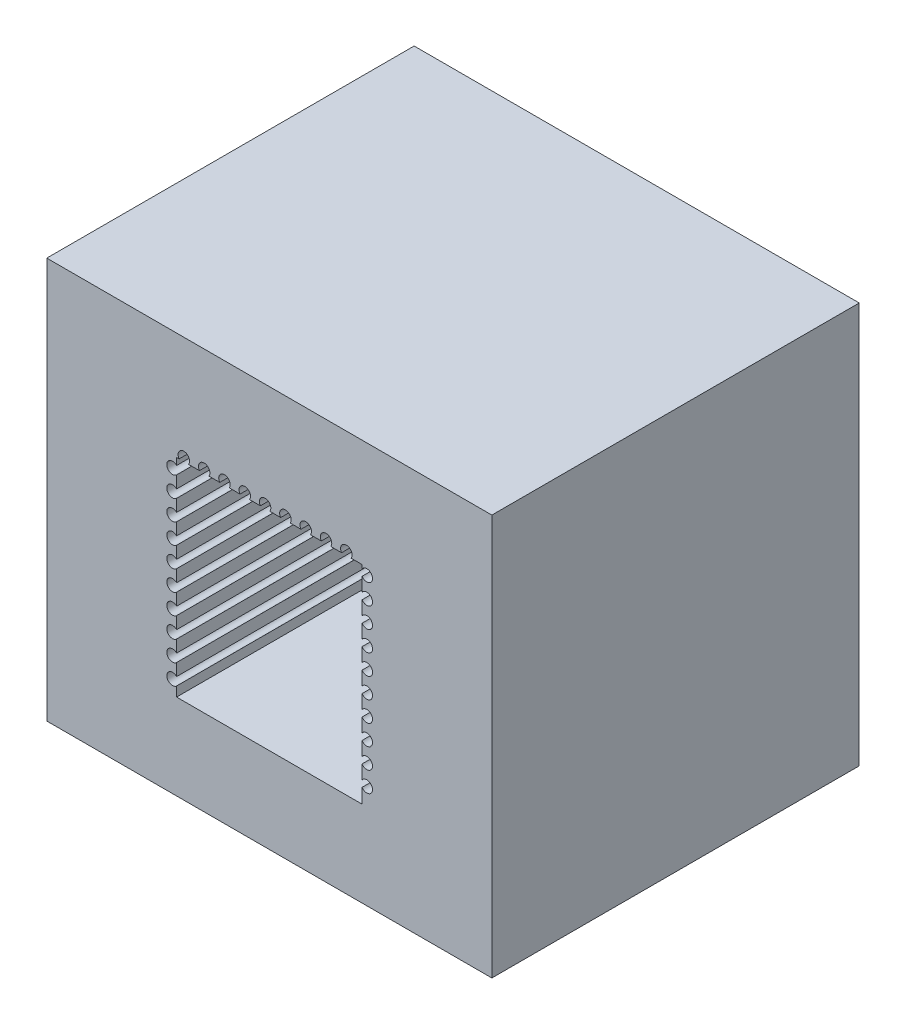
SolidWorks part; units mm, degrees
ref_plane "Front Plane" through (0, 0, 0) normal (0, 0, 1) x (1, 0, 0)
ref_plane "Top Plane" through (0, 0, 0) normal (0, 1, 0) x (1, 0, 0)
ref_plane "Right Plane" through (0, 0, 0) normal (1, 0, 0) x (0, 0, -1)
sketch "Sketch1" plane through (0, 0, 0) normal (0, 0, 1) x (1, 0, 0)
  line L1 (-252, 227) -> (252, 227)
  line L2 (-252, 227) -> (-252, -227)
  line L3 (-252, -227) -> (252, -227)
  line L4 (252, 227) -> (252, -227)
  line L5 (-252, 227) -> (252, -227) construction
  line L6 (-252, -227) -> (252, 227) construction
  point P0 (0, 0)
  dimension "D1" = 504
  dimension "D2" = 454
extrude "Boss-Extrude1" add sketch "Sketch1" against normal blind 416
sketch "Sketch2" plane through (0, 0, 0) normal (0, 0, 1) x (1, 0, 0)
  line L1 (-130, 130) -> (130, 130)
  line L2 (-130, 130) -> (-130, -130)
  line L3 (-130, -130) -> (130, -130)
  line L4 (130, 130) -> (130, -130)
  line L5 (-130, 130) -> (130, -130) construction
  line L6 (-130, -130) -> (130, 130) construction
  point P0 (0, 0)
  dimension "D1" = 260
  dimension "D2" = 260
extrude "Cut-Extrude1" cut sketch "Sketch2" against normal blind 260
sketch "Sketch5" plane through (0, 0, 0) normal (0, 0, 1) x (1, 0, 0)
  line L0 (-130, -130) -> (130, -130) construction
  line L1 (-130, 130) -> (-105, 130)
  line L2 (-130, 130) -> (-130, -130)
  line L3 (-130, -130) -> (-105, -130)
  line L4 (-105, 105) -> (-105, -130)
  line L5 (-130, -130) -> (130, -130) construction
  line L6 (130, 130) -> (105, 130)
  line L7 (130, 130) -> (130, -130)
  line L8 (130, -130) -> (105, -130)
  line L9 (105, 105) -> (105, -130)
  line L10 (-130, 130) -> (130, 130)
  line L11 (-130, 130) -> (130, 130)
  line L12 (-130, 130) -> (-130, 105)
  line L13 (-105, 105) -> (105, 105)
  line L14 (130, 130) -> (130, 105)
  line M1 (130, 130) -> (130, -130)
  line M2 (130, -130) -> (-130, -130)
  line M3 (-130, -130) -> (-130, 130)
  line M4 (-130, 130) -> (130, 130)
  dimension "D1" = 25
  dimension "D2" = 25
  dimension "D3" = 25
extrude "Boss-Extrude2" add sketch "Sketch5" against normal blind 260 contours L4 L13 L9 L7 L2 M2 M1 M4 M3
sketch "Sketch6" plane through (0, 0, 0) normal (0, 0, 1) x (1, 0, 0)
  circle A0 centre (-109.593, 92.4977) radius 6.5
  dimension "D1" = 13
extrude "Cut-Extrude2" cut sketch "Sketch6" against normal blind 260
sketch "Sketch7" plane through (0, 0, 0) normal (0, 0, 1) x (1, 0, 0)
  line L0 (0, 227) -> (0, -130) construction
  line L1 (252, 227) -> (-252, 227) construction
  line L2 (-105, -130) -> (105, -130) construction
  line L3 (-121.2933, 92.4977) -> (0, 92.4977) construction
  circle A0 centre (-109.593, 92.4977) radius 6.5 construction
  circle A1 centre (110.3716, 97.1096) radius 6.5
  dimension "D1" = 13
pattern_linear "LPattern3" count 10 spacing 23 along (0, -1, 0) of "Cut-Extrude2"
extrude "Cut-Extrude3" cut sketch "Sketch7" against normal blind 260
pattern_linear "LPattern4" count 10 spacing 23 along (0, -1, 0) of "Cut-Extrude3"
sketch "Sketch8" plane through (0, 0, 0) normal (0, 0, 1) x (1, 0, 0)
  circle A0 centre (-96.7866, 108.682) radius 6.5
  dimension "D1" = 13
extrude "Cut-Extrude4" cut sketch "Sketch8" against normal blind 260
pattern_linear "LPattern5" count 9 spacing 23 along (1, 0, 0) of "Cut-Extrude4"
